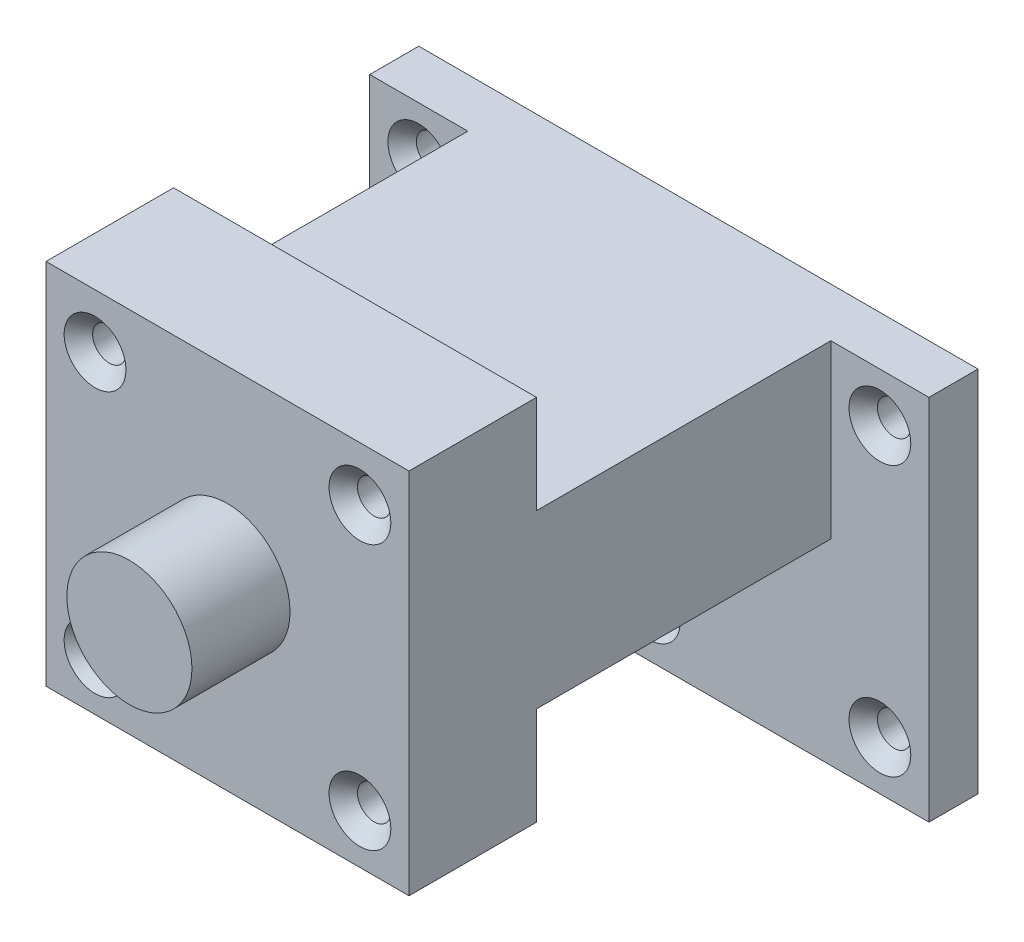
SolidWorks part; units mm, degrees
ref_plane "Plan de face" through (0, 0, 0) normal (0, 0, 1) x (1, 0, 0)
ref_plane "Plan de dessus" through (0, 0, 0) normal (0, 1, 0) x (1, 0, 0)
ref_plane "Plan de droite" through (0, 0, 0) normal (1, 0, 0) x (0, 0, -1)
sketch "Esquisse1" plane through (0, 0, 0) normal (0, 0, 1) x (1, 0, 0)
  line L2 (0, 0) -> (37, 0)
  line L3 (0, 0) -> (0, 37.5)
  line L4 (0, 37.5) -> (37, 37.5)
  line L5 (37, 0) -> (37, 37.5)
  dimension "D1" = 37.5
  dimension "D2" = 37
extrude "Boss.-Extru.1" add sketch "Esquisse1" along normal blind 48
sketch "Esquisse2" plane through (0, 0, 48) normal (0, 0, 1) x (1, 0, 0)
  line L0 (37, 0) -> (37, 37.5) construction
  line L4 (37, 37.5) -> (0, 37.5) construction
  circle A0 centre (18.5, 19) radius 6.375
  dimension "D3" = 12.75
  dimension "D1" = 18.5
  dimension "D2" = 18.5
extrude "Boss.-Extru.2" add sketch "Esquisse2" along normal blind 10
sketch "Esquisse3" plane through (0, 0, 48) normal (0, 0, 1) x (1, 0, 0)
  line L0 (37, 37.5) -> (0, 37.5) construction
  line L1 (0, 37.5) -> (0, 0) construction
  line L2 (37, 0) -> (37, 37.5) construction
  circle A0 centre (5, 32) radius 1.5
  circle A1 centre (32, 32) radius 1.5
  circle A2 centre (32, 5) radius 1.5
  circle A3 centre (5, 5) radius 1.5
  dimension "D3" = 3
  dimension "D5" = 3
  dimension "D9" = 3
  dimension "D11" = 3
  dimension "D1" = 5.5
  dimension "D2" = 5.5
  dimension "5" = 5
  dimension "D4" = 5
  dimension "D6" = 5
  dimension "D7" = 5
  dimension "D8" = 27
  dimension "D10" = 27
sketch "Esquisse6" plane through (0, 0, 0) normal (0, -1, 0) x (1, 0, 0)
  line L1 (0, 0) -> (10, 0)
  line L2 (0, 0) -> (0, 5)
  line L3 (0, 5) -> (10, 5)
  line L4 (10, 0) -> (10, 5)
  line L5 (37, 0) -> (27, 0)
  line L6 (37, 0) -> (37, 5)
  line L7 (37, 5) -> (27, 5)
  line L8 (27, 0) -> (27, 5)
  dimension "D1" = 10
  dimension "D2" = 5
  dimension "D3" = 10
  dimension "D4" = 5
extrude "Boss.-Extru.3" [suppressed] add sketch "Esquisse6" along normal blind 10
sketch "Esquisse7" plane through (0, 37.5, 0) normal (0, 1, 0) x (1, 0, 0)
  line L1 (0, 0) -> (10, 0)
  line L2 (0, 0) -> (0, -5)
  line L3 (0, -5) -> (10, -5)
  line L4 (10, 0) -> (10, -5)
  line L5 (37, 0) -> (27, 0)
  line L6 (37, 0) -> (37, -5)
  line L7 (37, -5) -> (27, -5)
  line L8 (27, 0) -> (27, -5)
  dimension "D1" = 5
  dimension "D2" = 5
  dimension "D3" = 10
  dimension "D4" = 10
extrude "Boss.-Extru.4" [suppressed] add sketch "Esquisse7" along normal blind 10
sketch "Esquisse8" [suppressed] plane through (0, 0, 5) normal (0, 0, 1) x (1, 0, 0)
  line L0 (37, -10) -> (27, -10) construction
  line L1 (37, -10) -> (37, 0) construction
  circle A0 centre (32, -5) radius 2.6226
  circle A1 centre (4.4036, -5.1811) radius 2.9344
  circle A2 centre (4.4036, 42.3532) radius 2.5459
  circle A3 centre (32.4325, 42.3532) radius 2.5419
  dimension "D1" = 5
  dimension "5" = 5
sketch "Esquisse10" plane through (0, 0, 0) normal (0, 0, -1) x (-1, 0, 0)
  line L0 (0, 37.5) -> (0, 0) construction
  line L1 (-37, 0) -> (-27, 0)
  line L2 (-37, 0) -> (-37, 10)
  line L3 (-37, 10) -> (-27, 10)
  line L4 (-27, 0) -> (-27, 10)
  line L5 (-37, 37.5) -> (0, 37.5)
  line L6 (-37, 37.5) -> (-37, 27.5)
  line L7 (-37, 27.5) -> (0, 27.5)
  line L8 (0, 37.5) -> (0, 27.5)
  line L13 (0, 0) -> (-10, 0)
  line L14 (0, 0) -> (0, 10)
  line L15 (0, 10) -> (-10, 10)
  line L16 (-10, 0) -> (-10, 10)
  point P10 (0, 27.1621)
  dimension "D1" = 10
  dimension "D5" = 10
  dimension "D6" = 10
  dimension "10" = 10
  dimension "D7" = 10
extrude "Enlèv. mat.-Extru.1" cut sketch "Esquisse10" against normal blind 30 from offset 5 offset against normal yes
hole_wizard "Fraisage pour vis à tête fraisée bombée M31" positions "Esquisse4" profile "Esquisse5" countersink size "M3" standard "ISO"
sketch "Esquisse4" plane through (0, 0, 48) normal (0, 0, 1) x (1, 0, 0)
  point P0 (5, 32)
  point P3 (32, 32)
  point P6 (32, 5)
  point P9 (5, 5)
sketch "Esquisse5" plane through (5, 32, 48) normal (1, 0, 0) x (0, -1, 0)
  line L0 (0, 0) -> (0, 14.0215)
  line L1 (0, 14.0215) -> (1.7, 13)
  line L2 (1.7, 13) -> (1.7, 1.45)
  line L3 (1.7, 1.45) -> (3.15, 0)
  line L5 (3.15, 0) -> (0, 0)
  line L6 (-1.7, 1.45) -> (-3.15, 0) construction
  line L10 (0, 14.0215) -> (-1.7, 13) construction
  line L11 (0, -6.35) -> (0, 107.95) construction
  dimension "Diamètre du perçage" = 3.4
  dimension "Profondeur du perçage" = 13
  dimension "Diamètre du fraisage entrant" = 6.3
  dimension "Angle du fraisage entrant" = 90
  dimension "Angle de pointe" = 118
sketch "Esquisse11" plane through (0, 0, 0) normal (0, 0, -1) x (-1, 0, 0)
  line L8 (-37, 27.5) -> (0, 27.5) construction
  line L9 (-37, 27.5) -> (-47, 27.5)
  line L12 (-47, 27.5) -> (-47, -10)
  line L13 (0, 27.5) -> (10, 27.5)
  line L16 (10, 27.5) -> (10, -10)
  line L22 (-47, -10) -> (10, -10)
  line L23 (0, 0) -> (-37, 0) construction
  line L25 (-37, 0) -> (0, 0)
  line L26 (-37, 27.5) -> (-37, 0)
  line L28 (0, 27.5) -> (0, 0)
  dimension "D1" = 10
  dimension "D2" = 10
  dimension "D3" = 10
extrude "Boss.-Extru.5" add sketch "Esquisse11" against normal blind 5
sketch "Esquisse12" plane through (0, 0, 0) normal (0, 0, -1) x (-1, 0, 0)
  line L1 (-37, 37.5) -> (0, 37.5)
  line L2 (-37, 37.5) -> (-37, 27.5)
  line L3 (-37, 27.5) -> (0, 27.5)
  line L4 (0, 37.5) -> (0, 27.5)
extrude "Enlèv. mat.-Extru.2" cut sketch "Esquisse12" against normal up to surface (5 mm away) up to face at (18.5, 32.5, 5)
sketch "Esquisse13" plane through (0, 0, 5) normal (0, 0, 1) x (1, 0, 0)
  line L0 (-10, 27.5) -> (0, 27.5) construction
  line L1 (-10, -10) -> (-10, 27.5) construction
  line L2 (47, -10) -> (-10, -10) construction
  line L3 (47, 27.5) -> (47, -10) construction
  line L6 (37, 27.5) -> (47, 27.5) construction
  circle A0 centre (-5, 22.5) radius 1.5
  circle A1 centre (-5, -5) radius 1.5
  circle A2 centre (18.5, -5) radius 1.5
  circle A3 centre (42, -5) radius 1.5
  circle A4 centre (42, 22.5) radius 1.5
  point P18 (-10, -7.695)
  point P21 (44.1929, 27.5)
  point P22 (43.9873, 27.5)
  dimension "D5" = 3
  dimension "D6" = 3
  dimension "D9" = 3
  dimension "D12" = 3
  dimension "D15" = 3
  dimension "D1" = 5
  dimension "D2" = 5
  dimension "D3" = 5
  dimension "D4" = 5
  dimension "D7" = 5
  dimension "D8" = 28.5
  dimension "D10" = 5
  dimension "D11" = 5
  dimension "D13" = 5
  dimension "D14" = 5
hole_wizard "Fraisage pour vis à tête fraisée bombée M32" positions "Esquisse14" profile "Esquisse15" countersink size "M3" standard "ISO"
sketch "Esquisse14" plane through (0, 0, 5) normal (0, 0, 1) x (1, 0, 0)
  point P0 (-5, 22.5)
  point P3 (-5, -5)
  point P6 (18.5, -5)
  point P9 (42, -5)
  point P12 (42, 22.5)
sketch "Esquisse15" plane through (-5, 22.5, 5) normal (1, 0, 0) x (0, -1, 0)
  line L0 (0, 0) -> (0, 6.0215)
  line L1 (0, 6.0215) -> (1.7, 5)
  line L2 (1.7, 5) -> (1.7, 1.45)
  line L3 (1.7, 1.45) -> (3.15, 0)
  line L5 (3.15, 0) -> (0, 0)
  line L6 (-1.7, 1.45) -> (-3.15, 0) construction
  line L10 (0, 6.0215) -> (-1.7, 5) construction
  line L11 (0, -6.35) -> (0, 107.95) construction
  dimension "Diamètre du perçage" = 3.4
  dimension "Profondeur du perçage" = 5
  dimension "Diamètre du fraisage entrant" = 6.3
  dimension "Angle du fraisage entrant" = 90
  dimension "Angle de pointe" = 118
